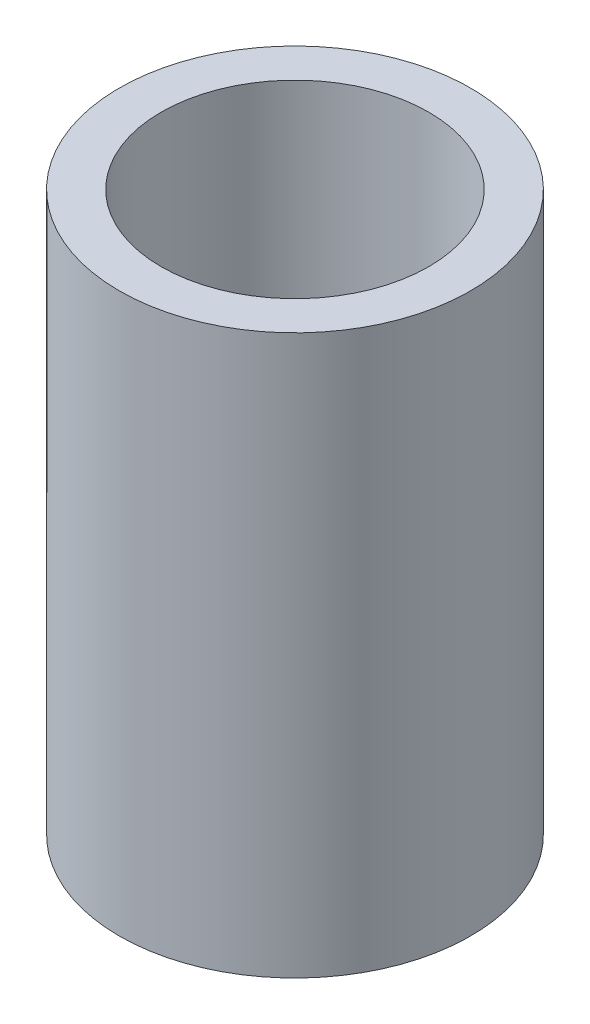
SolidWorks part; units mm, degrees
ref_plane "Front Plane" through (0, 0, 0) normal (0, 0, 1) x (1, 0, 0)
ref_plane "Top Plane" through (0, 0, 0) normal (0, 1, 0) x (1, 0, 0)
ref_plane "Right Plane" through (0, 0, 0) normal (1, 0, 0) x (0, 0, -1)
sketch "Sketch1" plane through (0, 0, 0) normal (0, 1, 0) x (1, 0, 0)
  circle A0 centre (0, 0) radius 52.5
  circle A1 centre (0, 0) radius 40
  dimension "D1" = 105
  dimension "D2" = 80
extrude "Boss-Extrude1" add sketch "Sketch1" along normal blind 167
sketch "Sketch2" plane through (0, 0, 0) normal (0, -1, 0) x (1, 0, 0)
  circle A0 centre (0, 0) radius 52.5
extrude "Boss-Extrude2" add sketch "Sketch2" against normal blind 5
